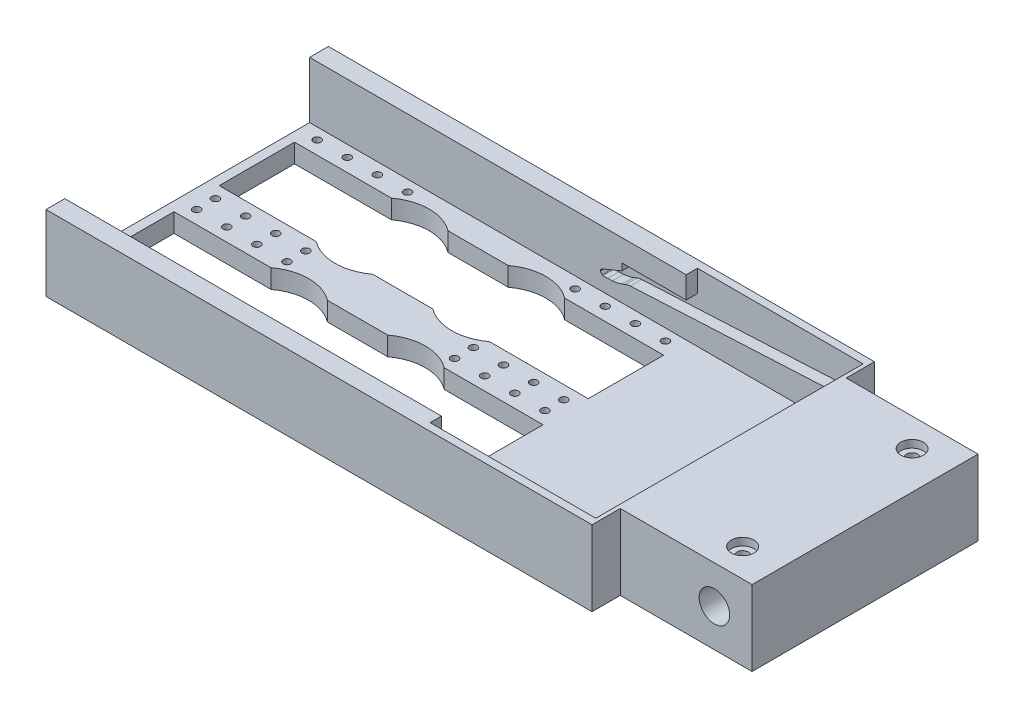
SolidWorks part; units mm, degrees
ref_plane "Front Plane" through (0, 0, 0) normal (0, 0, 1) x (1, 0, 0)
ref_plane "Top Plane" through (0, 0, 0) normal (0, 1, 0) x (1, 0, 0)
ref_plane "Right Plane" through (0, 0, 0) normal (1, 0, 0) x (0, 0, -1)
sketch "Sketch1" plane through (0, 0, 0) normal (0, 1, 0) x (1, 0, 0)
  line L1 (-90, 37.5) -> (90, 37.5)
  line L2 (-90, 37.5) -> (-90, -37.5)
  line L3 (-90, -37.5) -> (90, -37.5)
  line L4 (90, 37.5) -> (90, -37.5)
  line L5 (-90, 37.5) -> (90, -37.5) construction
  line L6 (-90, -37.5) -> (90, 37.5) construction
  circle A0 centre (80, 22.5) radius 1.5
  circle A1 centre (80, -22.5) radius 1.5
  point P0 (0, 0)
  dimension "D3" = 3
  dimension "D5" = 15
  dimension "D6" = 15
  dimension "D1" = 180
  dimension "D2" = 75
  dimension "D4" = 10
extrude "Boss-Extrude1" add sketch "Sketch1" along normal blind 20
sketch "Sketch2" plane through (0, 0, 37.5) normal (0, 0, 1) x (1, 0, 0)
  line L0 (90, 20) -> (90, 0) construction
  line L1 (-90, 20) -> (90, 20) construction
  line L2 (-90, 20) -> (40, 20) construction
  line L3 (-90, 20) -> (-90, 5) construction
  line L4 (-90, 5) -> (40, 5) construction
  line L5 (40, 20) -> (40, 5) construction
  line L6 (-90, 20) -> (40, 5) construction
  line L7 (-90, 5) -> (40, 20) construction
  line L8 (-90, 20) -> (-90, 0) construction
  circle A0 centre (80, 10) radius 4.05
  point P4 (90, 10)
  point P5 (-25, 12.5)
  dimension "D1" = 8.1
  dimension "D2" = 10
  dimension "D3" = 15
  dimension "D4" = 130
extrude "Cut-Extrude1" cut sketch "Sketch2" against normal through all
sketch "Sketch3" plane through (0, 20, 0) normal (0, 1, 0) x (1, 0, 0)
  line L0 (-90, 37.5) -> (-90, -37.5) construction
  line L2 (-85, 29.5) -> (-77, 29.5) construction
  line L3 (-85, 2.5) -> (-77, 2.5) construction
  line L4 (0, 0) -> (13.7346, 0) construction
  line L6 (-16.5, 29.5) -> (-8.5, 29.5) construction
  line L7 (-85, 29.5) -> (-85, 2.5) construction
  line L8 (-87.5, 26) -> (-61.75, 26)
  line L9 (-87.5, 26) -> (-87.5, 6)
  line L10 (-87.5, 6) -> (-61.75, 6)
  line L11 (10.5, 26) -> (10.5, 6)
  line L12 (-16.5, 2.5) -> (-8.5, 2.5) construction
  line L13 (-16.5, -2.5) -> (-8.5, -2.5) construction
  line L14 (-85, -29.5) -> (-85, -2.5) construction
  line L15 (-16.5, -29.5) -> (-8.5, -29.5) construction
  line L16 (-85, -2.5) -> (-77, -2.5) construction
  line L17 (-85, -29.5) -> (-77, -29.5) construction
  line L18 (10.5, -26) -> (10.5, -6)
  line L19 (-87.5, -6) -> (-61.75, -6)
  line L20 (-87.5, -26) -> (-87.5, -6)
  line L21 (-87.5, -26) -> (-61.75, -26)
  line L22 (-46.75, 6) -> (-30.75, 6)
  line L23 (-46.75, 26) -> (-30.75, 26)
  line L24 (-15.75, 26) -> (10.5, 26)
  line L25 (-15.75, 6) -> (10.5, 6)
  line L26 (-46.75, -6) -> (-30.75, -6)
  line L27 (-46.75, -26) -> (-30.75, -26)
  line L28 (-15.75, -6) -> (10.5, -6)
  line L29 (-15.75, -26) -> (10.5, -26)
  circle A0 centre (-85, 29.5) radius 1
  circle A1 centre (-85, 2.5) radius 1
  circle A2 centre (-77, 29.5) radius 1
  circle A3 centre (-69, 29.5) radius 1
  circle A4 centre (-61, 29.5) radius 1
  circle A11 centre (-77, 2.5) radius 1
  circle A12 centre (-69, 2.5) radius 1
  circle A13 centre (-61, 2.5) radius 1
  circle A50 centre (-16.5, 29.5) radius 1
  circle A51 centre (-16.5, 2.5) radius 1
  circle A52 centre (-8.5, 29.5) radius 1
  circle A53 centre (-0.5, 29.5) radius 1
  circle A54 centre (7.5, 29.5) radius 1
  circle A55 centre (-8.5, 2.5) radius 1
  circle A56 centre (-0.5, 2.5) radius 1
  circle A57 centre (7.5, 2.5) radius 1
  circle A58 centre (7.5, -2.5) radius 1
  circle A59 centre (-0.5, -2.5) radius 1
  circle A60 centre (-8.5, -2.5) radius 1
  circle A61 centre (7.5, -29.5) radius 1
  circle A62 centre (-0.5, -29.5) radius 1
  circle A63 centre (-8.5, -29.5) radius 1
  circle A64 centre (-16.5, -2.5) radius 1
  circle A65 centre (-16.5, -29.5) radius 1
  circle A66 centre (-61, -2.5) radius 1
  circle A67 centre (-69, -2.5) radius 1
  circle A68 centre (-77, -2.5) radius 1
  circle A69 centre (-61, -29.5) radius 1
  circle A70 centre (-69, -29.5) radius 1
  circle A71 centre (-77, -29.5) radius 1
  circle A72 centre (-85, -2.5) radius 1
  circle A73 centre (-85, -29.5) radius 1
  arc A74 (-61.75, 6) -> (-46.75, 6) centre (-54.25, 16) ccw
  arc A75 (-30.75, 6) -> (-15.75, 6) centre (-23.25, 16) ccw
  arc A76 (-30.75, -26) -> (-15.75, -26) centre (-23.25, -16) ccw
  arc A77 (-61.75, -26) -> (-46.75, -26) centre (-54.25, -16) ccw
  arc A78 (-46.75, 26) -> (-61.75, 26) centre (-54.25, 16) ccw
  arc A79 (-15.75, 26) -> (-30.75, 26) centre (-23.25, 16) ccw
  arc A80 (-46.75, -6) -> (-61.75, -6) centre (-54.25, -16) ccw
  arc A81 (-15.75, -6) -> (-30.75, -6) centre (-23.25, -16) ccw
  point P96 (-87.5, 16)
  point P97 (-85, 16)
  dimension "D1" = 2
  dimension "D3" = 5
  dimension "D4" = 27
  dimension "D12" = 2
  dimension "D19" = 25
  dimension "D2" = 5
  dimension "D6" = 8
  dimension "D8" = 8
  dimension "D9" = 20
  dimension "D10" = 98
  dimension "D11" = 2.5
  dimension "D13" = 44.5
  dimension "D15" = 8
  dimension "D17" = 8
  dimension "D20" = 10
  dimension "D21" = 10
  dimension "D22" = 6.75
  dimension "D23" = 6.75
  dimension "D5" = 4
  dimension "D7" = 4
  dimension "D14" = 4
  dimension "D16" = 4
extrude "Cut-Extrude2" cut sketch "Sketch3" against normal through all
sketch "Sketch6" plane through (0, 20, 0) normal (0, 1, 0) x (1, 0, 0)
  line L0 (-90, -37.5) -> (90, -37.5) construction
  line L1 (55, 37.5) -> (90, 37.5)
  line L2 (55, 37.5) -> (55, 30)
  line L3 (55, 30) -> (90, 30)
  line L4 (90, 37.5) -> (90, 30)
  line L5 (55, 37.5) -> (90, 30) construction
  line L6 (55, 30) -> (90, 37.5) construction
  line L7 (55, -30) -> (90, -30)
  line L8 (55, -30) -> (55, -37.5)
  line L9 (55, -37.5) -> (90, -37.5)
  line L10 (90, -30) -> (90, -37.5)
  line L11 (55, -30) -> (90, -37.5) construction
  line L12 (55, -37.5) -> (90, -30) construction
  line L14 (90, -37.5) -> (90, 37.5) construction
  line L15 (90, 37.5) -> (-90, 37.5) construction
  point P0 (72.5, 33.75)
  point P5 (72.5, -33.75)
  dimension "D1" = 60
  dimension "D2" = 35
extrude "Cut-Extrude3" cut sketch "Sketch6" against normal through all
sketch "Sketch7" plane through (0, 20, 0) normal (0, 1, 0) x (1, 0, 0)
  line L0 (-90, 37.5) -> (-90, -37.5) construction
  line L1 (-90, 32.5) -> (50, 32.5)
  line L2 (-90, 32.5) -> (-90, -32.5)
  line L3 (-90, -32.5) -> (50, -32.5)
  line L4 (50, 32.5) -> (50, -32.5)
  line L5 (-90, 32.5) -> (50, -32.5) construction
  line L6 (-90, -32.5) -> (50, 32.5) construction
  point P0 (-20, 0)
  dimension "D1" = 65
  dimension "D2" = 140
extrude "Cut-Extrude4" cut sketch "Sketch7" against normal blind 15
sketch "Sketch8" plane through (0, 0, 0) normal (0, 0, 1) x (1, 0, 0)
  line L0 (60, 8.73) -> (-110.2739, 8.73) construction
  line L1 (-90, 0) -> (55, 0) construction
  line L2 (15.8524, 13.8221) -> (23, 14.1931)
  line L3 (15.8524, 13.8221) -> (-5.4943, 12.7138)
  line L4 (55, 0) -> (55, 20) construction
  line L5 (15.943, 11.0473) -> (54, 12.9563)
  line L6 (23, 14.1931) -> (23, 20)
  line L7 (-90, 20) -> (55, 20) construction
  line L8 (23, 20) -> (54, 20)
  line L9 (54, 20) -> (54, 12.9563)
  line L10 (-4.7867, 10.0075) -> (15.943, 11.0473)
  line L11 (-11.571, 10.4956) -> (-7.0679, 12.3585)
  line L12 (-10.8715, 8.73) -> (-9.6129, 8.8054)
  line L13 (-12.794, 9.4393) -> (-12.355, 8.8431)
  line L14 (-12.8018, 9.4838) -> (-12.7342, 9.7139)
  line L15 (-12.4274, 10.0693) -> (-11.571, 10.4956)
  line L16 (-12.5392, 9.9849) -> (-12.6502, 9.8631)
  line L17 (-12.1674, 8.7403) -> (-12.0783, 8.7343)
  line L18 (-6.8748, 9.4125) -> (-6.0777, 9.7277)
  arc A0 (-12.5392, 9.9849) -> (-12.4274, 10.0693) centre (-12.2576, 9.7282) cw
  arc A1 (-12.0783, 8.7343) -> (-10.8715, 8.73) centre (-11.4408, 18.238) ccw
  arc A2 (-7.0679, 12.3585) -> (-5.4943, 12.7138) centre (-5.2473, 7.9577) cw
  arc A3 (-12.7342, 9.7139) -> (-12.6502, 9.8631) centre (-12.3687, 9.6064) cw
  arc A4 (-12.794, 9.4393) -> (-12.8018, 9.4838) centre (-12.7531, 9.4694) cw
  arc A5 (-12.355, 8.8431) -> (-12.1674, 8.7403) centre (-12.1504, 8.9937) ccw
  arc A6 (-9.6129, 8.8054) -> (-6.8748, 9.4125) centre (-10.1443, 17.6795) ccw
  arc A7 (-6.0777, 9.7277) -> (-4.7867, 10.0075) centre (-4.5831, 5.9486) cw
  line B0 (-5.4943, 12.7138) -> (15.8524, 13.8221) construction
  line B1 (-4.7867, 10.0075) -> (15.943, 11.0473) construction
  line B2 (16.7875, 12.9343) -> (16.7875, 11.9352) construction
  line B3 (-11.571, 10.4956) -> (-7.0679, 12.3585) construction
  line B4 (-6.8748, 9.4125) -> (-6.0777, 9.7277) construction
  line B5 (-10.8715, 8.73) -> (-9.6129, 8.8054) construction
  line B6 (-12.794, 9.4393) -> (-12.355, 8.8431) construction
  line B7 (-12.6502, 9.8631) -> (-12.5392, 9.9849) construction
  line B8 (-12.4274, 10.0693) -> (-11.571, 10.4956) construction
  line B9 (-12.8018, 9.4838) -> (-12.7342, 9.7139) construction
  line B10 (-12.1674, 8.7403) -> (-12.0783, 8.7343) construction
  arc B11 (16.7875, 12.9343) -> (15.8524, 13.8221) centre (15.8985, 12.9343) ccw construction
  arc B12 (16.7875, 11.9352) -> (15.943, 11.0473) centre (15.8985, 11.9352) cw construction
  arc B13 (-6.8748, 9.4125) -> (-9.6129, 8.8054) centre (-10.1443, 17.6795) cw construction
  arc B14 (-6.0777, 9.7277) -> (-4.7867, 10.0075) centre (-4.5831, 5.9486) cw construction
  arc B15 (-7.0679, 12.3585) -> (-5.4943, 12.7138) centre (-5.2473, 7.9577) cw construction
  arc B16 (-12.7342, 9.7139) -> (-12.6502, 9.8631) centre (-12.3687, 9.6064) cw construction
  arc B17 (-12.4274, 10.0693) -> (-12.5392, 9.9849) centre (-12.2576, 9.7282) ccw construction
  arc B18 (-12.8018, 9.4838) -> (-12.794, 9.4393) centre (-12.7531, 9.4694) ccw construction
  arc B19 (-12.1674, 8.7403) -> (-12.355, 8.8431) centre (-12.1504, 8.9937) cw construction
  arc B20 (-12.0783, 8.7343) -> (-10.8715, 8.73) centre (-11.4408, 18.238) ccw construction
  dimension "D1" = 8.73
  dimension "D2" = 38.2125
  dimension "D3" = 32
  dimension "D4" = 1
sketch_block_instance "ScanOutline-10"
sketch_block "ScanOutline" parameters "D1"=0.889, "D2"=8.89, "D3"=4.064, "D4"=4.7625, "D5"=0.381, "D6"=0.0508, "D7"=0.254, "D8"=9.525
extrude "Cut-Extrude5" [suppressed] cut sketch "Sketch8" against normal mid plane 72
sketch "Sketch9" plane through (0, 20, 0) normal (0, 1, 0) x (1, 0, 0)
  line L1 (90, 30) -> (55, 30)
  line L2 (90, 30) -> (90, -30)
  line L3 (90, -30) -> (55, -30)
  line L4 (55, 30) -> (55, -30)
extrude "Cut-Extrude6" [suppressed] cut sketch "Sketch9" against normal through all
sketch "Sketch10" plane through (0, 0, 0) normal (0, 0, 1) x (1, 0, 0)
  line L0 (59.9991, 8.73) -> (-110.2748, 8.73) construction
  line L7 (-4.7874, 10.0064) -> (15.9425, 11.0426)
  line L8 (-11.5716, 10.4957) -> (-7.0683, 12.3578)
  line L9 (-10.8725, 8.73) -> (-9.6139, 8.8051)
  line L10 (-12.7948, 9.4397) -> (-12.3559, 8.8434)
  line L11 (-12.8026, 9.4841) -> (-12.735, 9.7142)
  line L12 (-12.4281, 10.0696) -> (-11.5716, 10.4957)
  line L13 (-12.5399, 9.9852) -> (-12.651, 9.8634)
  line L14 (-12.1684, 8.7405) -> (-12.0793, 8.7345)
  line L15 (-6.8756, 9.4118) -> (-6.0785, 9.7269)
  line L16 (-90, 0) -> (55, 0) construction
  line L17 (15.9425, 11.0426) -> (54, 12.945)
  line L19 (10, 14.1872) -> (-7.0683, 14.1872)
  line L20 (-7.0683, 14.1872) -> (-7.0683, 12.3578)
  line L21 (55, 0) -> (55, 20) construction
  line L22 (10, 14.1872) -> (10, 20)
  line L23 (-90, 20) -> (55, 20) construction
  line L24 (54, 20) -> (54, 12.945)
  line L25 (55, 0) -> (55, 20) construction
  line L26 (10, 20) -> (54, 20)
  arc A0 (-12.5399, 9.9852) -> (-12.4281, 10.0696) centre (-12.2584, 9.7285) cw
  arc A1 (-12.0793, 8.7345) -> (-10.8725, 8.73) centre (-11.4401, 18.2381) ccw
  arc A3 (-12.735, 9.7142) -> (-12.651, 9.8634) centre (-12.3695, 9.6067) cw
  arc A4 (-12.7948, 9.4397) -> (-12.8026, 9.4841) centre (-12.7539, 9.4698) cw
  arc A5 (-12.3559, 8.8434) -> (-12.1684, 8.7405) centre (-12.1513, 8.994) ccw
  arc A6 (-9.6139, 8.8051) -> (-6.8756, 9.4118) centre (-10.1437, 17.6793) ccw
  arc A7 (-6.0785, 9.7269) -> (-4.7874, 10.0064) centre (-4.5845, 5.9475) cw
  line B0 (-5.4945, 12.7129) -> (15.8524, 13.8174) construction
  line B1 (-4.7874, 10.0064) -> (15.9425, 11.0426) construction
  line B2 (16.7873, 12.9294) -> (16.7871, 11.9304) construction
  line B3 (-11.5716, 10.4957) -> (-7.0683, 12.3578) construction
  line B4 (-6.8756, 9.4118) -> (-6.0785, 9.7269) construction
  line B5 (-10.8725, 8.73) -> (-9.6139, 8.8051) construction
  line B6 (-12.7948, 9.4397) -> (-12.3559, 8.8434) construction
  line B7 (-12.651, 9.8634) -> (-12.5399, 9.9852) construction
  line B8 (-12.4281, 10.0696) -> (-11.5716, 10.4957) construction
  line B9 (-12.8026, 9.4841) -> (-12.735, 9.7142) construction
  line B10 (-12.1684, 8.7405) -> (-12.0793, 8.7345) construction
  arc B11 (16.7873, 12.9294) -> (15.8524, 13.8174) centre (15.8983, 12.9296) ccw construction
  arc B12 (16.7871, 11.9304) -> (15.9425, 11.0426) centre (15.8981, 11.9305) cw construction
  arc B13 (-6.8756, 9.4118) -> (-9.6139, 8.8051) centre (-10.1437, 17.6793) cw construction
  arc B14 (-6.0785, 9.7269) -> (-4.7874, 10.0064) centre (-4.5845, 5.9475) cw construction
  arc B15 (-7.0683, 12.3578) -> (-5.4945, 12.7129) centre (-5.2484, 7.9567) cw construction
  arc B16 (-12.735, 9.7142) -> (-12.651, 9.8634) centre (-12.3695, 9.6067) cw construction
  arc B17 (-12.4281, 10.0696) -> (-12.5399, 9.9852) centre (-12.2584, 9.7285) ccw construction
  arc B18 (-12.8026, 9.4841) -> (-12.7948, 9.4397) centre (-12.7539, 9.4698) ccw construction
  arc B19 (-12.1684, 8.7405) -> (-12.3559, 8.8434) centre (-12.1513, 8.994) cw construction
  arc B20 (-12.0793, 8.7345) -> (-10.8725, 8.73) centre (-11.4401, 18.2381) ccw construction
  dimension "D1" = 8.73
  dimension "D2" = 90.01
  dimension "D3" = 39.0575
  dimension "D4" = 1
  dimension "D5" = 45
  dimension "D6" = 1.8294
sketch_block_instance "ScanOutline-14"
sketch "Sketch11" plane through (0, 20, 0) normal (0, 1, 0) x (1, 0, 0)
  circle A0 centre (80, 22.5) radius 3
  circle A1 centre (80, -22.5) radius 3
  dimension "D1" = 6
  dimension "D2" = 6
extrude "Cut-Extrude7" cut sketch "Sketch11" against normal blind 2
extrude "Cut-Extrude8" cut sketch "Sketch10" against normal mid plane 71 contours L7 L17 L24 L26 L22 L19 L20 L8 L12 A0 L13 A3 L11 A4 L10 A5 L14 A1 L9 A6 L15 A7
